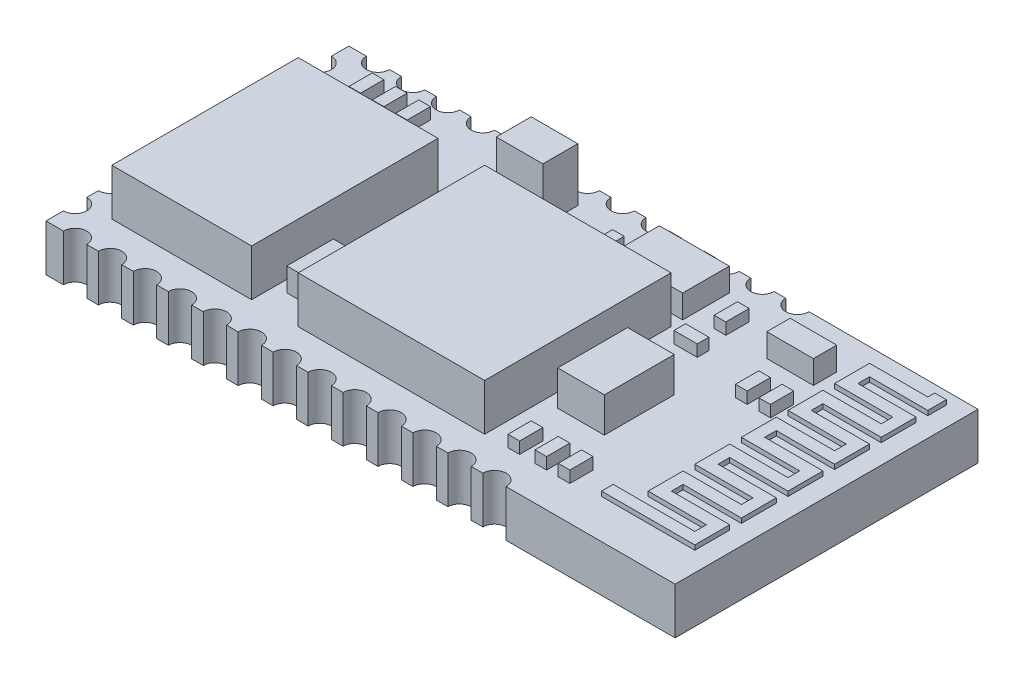
SolidWorks part; units mm, degrees
ref_plane "Front Plane" through (0, 0, 0) normal (0, 0, 1) x (1, 0, 0)
ref_plane "Top Plane" through (0, 0, 0) normal (0, 1, 0) x (1, 0, 0)
ref_plane "Right Plane" through (0, 0, 0) normal (1, 0, 0) x (0, 0, -1)
sketch "Sketch1" plane through (0, 0, 0) normal (0, 1, 0) x (1, 0, 0)
  line L1 (13.5, -6.5) -> (-13.5, -6.5)
  line L2 (13.5, -6.5) -> (13.5, 6.5)
  line L3 (13.5, 6.5) -> (-13.5, 6.5)
  line L4 (-13.5, -6.5) -> (-13.5, 6.5)
  line L5 (13.5, -6.5) -> (-13.5, 6.5) construction
  line L6 (13.5, 6.5) -> (-13.5, -6.5) construction
  point P0 (0, 0)
  dimension "D1" = 13
  dimension "D2" = 27
extrude "Boss-Extrude1" add sketch "Sketch1" along normal blind 2
sketch "Sketch2" plane through (0, 2, 0) normal (0, 1, 0) x (1, 0, 0)
  line L0 (-13.5, 6.5) -> (-13.5, -6.5) construction
  circle A0 centre (-13.5, 5.25) radius 0.5
  circle A1 centre (-13.5, 3.75) radius 0.5
  circle A2 centre (-13.5, 2.25) radius 0.5
  circle A3 centre (-13.5, 0.75) radius 0.5
  circle A4 centre (-13.5, -0.75) radius 0.5
  circle A5 centre (-13.5, -2.25) radius 0.5
  circle A6 centre (-13.5, -3.75) radius 0.5
  circle A7 centre (-13.5, -5.25) radius 0.5
  dimension "D1" = 1.25
  dimension "D2" = 2.75
  dimension "D3" = 4.25
  dimension "D4" = 5.75
  dimension "D5" = 7.25
  dimension "D6" = 8.75
  dimension "D7" = 10.25
  dimension "D8" = 11.75
extrude "Cut-Extrude7" cut sketch "Sketch2" against normal blind 2
sketch "Sketch9" plane through (0, 2, 0) normal (0, 1, 0) x (1, 0, 0)
  line L0 (13.5, 6.5) -> (-13.5, 6.5) construction
  circle A0 centre (-12.25, 6.5) radius 0.5
  circle A1 centre (-10.75, 6.5) radius 0.5
  circle A2 centre (-9.25, 6.5) radius 0.5
  circle A3 centre (-7.75, 6.5) radius 0.5
  circle A4 centre (-6.25, 6.5) radius 0.5
  circle A5 centre (-4.75, 6.5) radius 0.5
  circle A6 centre (-3.25, 6.5) radius 0.5
  circle A7 centre (-1.75, 6.5) radius 0.5
  circle A8 centre (-0.25, 6.5) radius 0.5
  circle A9 centre (1.25, 6.5) radius 0.5
  circle A10 centre (2.75, 6.5) radius 0.5
  circle A11 centre (4.25, 6.5) radius 0.5
  circle A12 centre (5.75, 6.5) radius 0.5
  circle A13 centre (-1.75, -6.5) radius 0.5
  circle A14 centre (-0.25, -6.5) radius 0.5
  circle A15 centre (-3.25, -6.5) radius 0.5
  circle A16 centre (2.75, -6.5) radius 0.5
  circle A17 centre (-7.75, -6.5) radius 0.5
  circle A18 centre (1.25, -6.5) radius 0.5
  circle A19 centre (-9.25, -6.5) radius 0.5
  circle A20 centre (-6.25, -6.5) radius 0.5
  circle A21 centre (4.25, -6.5) radius 0.5
  circle A22 centre (-12.25, -6.5) radius 0.5
  circle A23 centre (-10.75, -6.5) radius 0.5
  circle A24 centre (-4.75, -6.5) radius 0.5
  circle A25 centre (5.75, -6.5) radius 0.5
  dimension "D1" = 1.25
  dimension "D2" = 2.75
  dimension "D3" = 4.25
  dimension "D4" = 5.75
  dimension "D5" = 7.25
  dimension "D6" = 8.75
  dimension "D7" = 10.25
  dimension "D8" = 11.75
  dimension "D9" = 13.25
  dimension "D10" = 14.75
  dimension "D11" = 16.25
  dimension "D12" = 17.75
  dimension "D13" = 19.25
extrude "Cut-Extrude9" cut sketch "Sketch9" against normal blind 2
sketch "Sketch10" plane through (0, 2, 0) normal (0, 1, 0) x (1, 0, 0)
  line L1 (-12.1586, 2.9835) -> (-6.1586, 2.9835)
  line L2 (-12.1586, 2.9835) -> (-12.1586, -5.0165)
  line L3 (-12.1586, -5.0165) -> (-6.1586, -5.0165)
  line L4 (-6.1586, 2.9835) -> (-6.1586, -5.0165)
  line L5 (-4.1586, 2.9835) -> (3.8414, 2.9835)
  line L6 (-4.1586, 2.9835) -> (-4.1586, -5.0165)
  line L7 (-4.1586, -5.0165) -> (3.8414, -5.0165)
  line L8 (3.8414, 2.9835) -> (3.8414, -5.0165)
  dimension "D1" = 6
  dimension "D2" = 8
  dimension "D3" = 2
  dimension "D4" = 8
  dimension "D5" = 2
extrude "Boss-Extrude2" add sketch "Sketch10" along normal blind 2
sketch "Sketch12" plane through (0, 2, 0) normal (0, 1, 0) x (1, 0, 0)
  line L0 (3.8414, 2.9835) -> (-4.1586, 2.9835) construction
  line L1 (0.8414, 5.4835) -> (3.8414, 5.4835)
  line L2 (0.8414, 5.4835) -> (0.8414, 3.4835)
  line L3 (0.8414, 3.4835) -> (3.8414, 3.4835)
  line L4 (3.8414, 5.4835) -> (3.8414, 3.4835)
  line L6 (3.8414, -5.0165) -> (3.8414, 2.9835) construction
  dimension "D1" = 2
  dimension "D2" = 3
  dimension "D3" = 0.5
  dimension "D4" = 0
extrude "Boss-Extrude3" add sketch "Sketch12" along normal blind 1
sketch "Sketch13" plane through (0, 2, 0) normal (0, 1, 0) x (1, 0, 0)
  line L0 (0.8414, 5.4835) -> (0.8414, 3.4835) construction
  line L1 (-4.6586, 5.4835) -> (-2.6586, 5.4835)
  line L2 (-4.6586, 5.4835) -> (-4.6586, 3.9835)
  line L3 (-4.6586, 3.9835) -> (-2.6586, 3.9835)
  line L4 (-2.6586, 5.4835) -> (-2.6586, 3.9835)
  line L5 (0.8414, 5.4835) -> (0.8414, 3.4835) construction
  line L7 (3.8414, 2.9835) -> (-4.1586, 2.9835) construction
  point P9 (0.8414, 4.4835)
  dimension "D1" = 1.5
  dimension "D2" = 2
  dimension "D3" = 3.5
  dimension "D4" = 1
extrude "Boss-Extrude4" add sketch "Sketch13" along normal blind 2.3
sketch "Sketch14" plane through (0, 2, 0) normal (0, 1, 0) x (1, 0, 0)
  line L0 (-13.5, 6.5) -> (-13.5, 5.75) construction
  line L1 (-11, 4.5) -> (-11.5, 4.5)
  line L2 (-11, 4.5) -> (-11, 5.5)
  line L3 (-11, 5.5) -> (-11.5, 5.5)
  line L4 (-11.5, 4.5) -> (-11.5, 5.5)
  line L5 (-10, 4.5) -> (-10, 5.5)
  line L6 (-10.5, 4.5) -> (-10.5, 5.5)
  line L7 (-10, 4.5) -> (-10.5, 4.5)
  line L8 (-9.5, 4.5) -> (-9.5, 5.5)
  line L9 (-9, 4.5) -> (-9.5, 4.5)
  line L10 (-9, 4.5) -> (-9, 5.5)
  line L11 (-9, 5.5) -> (-9.5, 5.5)
  line L12 (6.5, -5.0165) -> (6.5, -4.0165)
  line L13 (7.5, -5.0165) -> (7.5, -4.0165)
  line L14 (7.5, -4.0165) -> (7, -4.0165)
  line L15 (6.5, -4.0165) -> (6, -4.0165)
  line L16 (6.5, -5.0165) -> (6, -5.0165)
  line L17 (7.5, -5.0165) -> (7, -5.0165)
  line L18 (7, -5.0165) -> (7, -4.0165)
  line L19 (6, -5.0165) -> (6, -4.0165)
  line L20 (5.3414, -5.0165) -> (4.8414, -5.0165)
  line L21 (5.3414, -5.0165) -> (5.3414, -4.0165)
  line L22 (4.8414, -5.0165) -> (4.8414, -4.0165)
  line L23 (5.3414, -4.0165) -> (4.8414, -4.0165)
  line L24 (9.3661, 2.7256) -> (8.8661, 2.7256)
  line L25 (9.3661, 1.7256) -> (8.8661, 1.7256)
  line L26 (8.8661, 1.7256) -> (8.8661, 2.7256)
  line L27 (9.3661, 1.7256) -> (9.3661, 2.7256)
  line L28 (8.3661, 1.7256) -> (8.3661, 2.7256)
  line L29 (8.3661, 1.7256) -> (7.8661, 1.7256)
  line L30 (7.8661, 1.7256) -> (7.8661, 2.7256)
  line L31 (8.3661, 2.7256) -> (7.8661, 2.7256)
  line L32 (-5.4086, 2.5) -> (-5.4086, 3.5)
  line L33 (-4.9086, 2.5) -> (-5.4086, 2.5)
  line L34 (-4.9086, 3.5) -> (-5.4086, 3.5)
  line L35 (-4.9086, 2.5) -> (-4.9086, 3.5)
  line L36 (13.5, -6.5) -> (13.5, 6.5) construction
  line L37 (-5.25, 6.5) -> (-5.75, 6.5) construction
  line L38 (3.8414, -5.0165) -> (3.8414, 2.9835) construction
  line L39 (4.8414, 3.8366) -> (4.8414, 4.8366)
  line L40 (-4.9086, 0.5) -> (-5.4086, 0.5)
  line L41 (-5.4086, -0.5) -> (-5.4086, 0.5)
  line L42 (-4.9086, -0.5) -> (-4.9086, 0.5)
  line L43 (-4.9086, -0.5) -> (-5.4086, -0.5)
  line L44 (-4.9086, -4.1379) -> (-4.9086, -2.6379)
  line L45 (-4.9086, -2.6379) -> (-5.4086, -2.6379)
  line L46 (-5.4086, -4.1379) -> (-5.4086, -2.6379)
  line L47 (-4.9086, -4.1379) -> (-5.4086, -4.1379)
  line L48 (-6.1586, -5.0165) -> (-6.1586, 2.9835) construction
  line L49 (5.3414, 4.8366) -> (4.8414, 4.8366)
  line L50 (5.3414, 3.8366) -> (5.3414, 4.8366)
  line L51 (5.3414, 3.8366) -> (4.8414, 3.8366)
  line L52 (-0.0202, 3.8366) -> (-0.5202, 3.8366)
  line L53 (-0.0202, 4.8366) -> (-0.5202, 4.8366)
  line L54 (-0.0202, 3.8366) -> (-0.0202, 4.8366)
  line L55 (-0.5202, 3.8366) -> (-0.5202, 4.8366)
  line L56 (7.5, 4.196) -> (7.5, 3.696)
  line L57 (9, 3.696) -> (7.5, 3.696)
  line L58 (9, 4.196) -> (7.5, 4.196)
  line L59 (9, 4.196) -> (9, 3.696)
  line L60 (5.5459, 2.9031) -> (4.5459, 2.9031)
  line L61 (4.5459, -0.6918) -> (5.5459, -0.6918)
  line L62 (4.5459, -0.6918) -> (4.5459, -2.6918)
  line L63 (4.5459, -2.6918) -> (5.5459, -2.6918)
  line L64 (5.5459, -0.6918) -> (5.5459, -2.6918)
  line L65 (5.5459, 2.4031) -> (4.5459, 2.4031)
  line L66 (4.5459, 2.9031) -> (4.5459, 2.4031)
  line L67 (5.5459, 2.9031) -> (5.5459, 2.4031)
  line L68 (-10.5, 5.5) -> (-10, 5.5)
  line L69 (-9.5, 5.5) -> (-9, 5.5)
  dimension "D1" = 0.5
  dimension "D2" = 1
  dimension "D3" = 2
  dimension "D4" = 1
  dimension "D5" = 1
  dimension "D6" = 0.5
  dimension "D7" = 1
  dimension "D8" = 0.5
  dimension "D9" = 0.5
  dimension "D10" = 0.5
  dimension "D11" = 0.5
  dimension "D12" = 1
  dimension "D13" = 0.5
  dimension "D14" = 0.75
  dimension "D15" = 1
  dimension "D16" = 1
  dimension "D17" = 0.5
  dimension "D18" = 1
  dimension "D19" = 0.5
  dimension "D20" = 6
  dimension "D21" = 0.75
  dimension "D22" = 0.75
  dimension "D23" = 3
  dimension "D24" = 1
  dimension "D25" = 2
  dimension "D26" = 1
  dimension "D27" = 1.5
  dimension "D28" = 1
  dimension "D29" = 2
extrude "Boss-Extrude6" add sketch "Sketch14" along normal blind 0.5 contours L10 L11 L8 L9 | L43 L42 L40 L41 | L51 L50 L49 L39 | L28 L31 L30 L29 | L25 L27 L24 L26 | L19 L16 L12 L15 | L2 L3 L4 L1 | L6 L68 L5 L7 | L54 L53 L55 L52 | L32 L34 L35 L33 | L60 L66 L65 L67 | L18 L14 L13 L17 | L21 L23 L22 L20
sketch "Sketch15" plane through (0, 2, 0) normal (0, 1, 0) x (1, 0, 0)
  line L0 (7.0844, 3.8532) -> (7.0844, 4.8532)
  line L1 (-5.6604, -2.0048) -> (-4.6604, -2.0048)
  line L2 (-5.6604, -2.0048) -> (-5.6604, -4.0048)
  line L3 (-5.6604, -4.0048) -> (-4.6604, -4.0048)
  line L4 (-4.6604, -2.0048) -> (-4.6604, -4.0048)
  line L5 (7.0844, 3.8532) -> (9.0844, 3.8532)
  line L6 (7.0844, 4.8532) -> (9.0844, 4.8532)
  line L7 (9.0844, 3.8532) -> (9.0844, 4.8532)
  dimension "D1" = 1
  dimension "D2" = 2
  dimension "D3" = 1
  dimension "D4" = 2
extrude "Boss-Extrude7" add sketch "Sketch15" along normal blind 1
sketch "Sketch16" plane through (0, 2, 0) normal (0, 1, 0) x (1, 0, 0)
  line L1 (4.4442, 0.5186) -> (6.4442, 0.5186)
  line L2 (4.4442, 0.5186) -> (4.4442, -2.4814)
  line L3 (4.4442, -2.4814) -> (6.4442, -2.4814)
  line L4 (6.4442, 0.5186) -> (6.4442, -2.4814)
  dimension "D1" = 2
  dimension "D2" = 3
extrude "Boss-Extrude8" add sketch "Sketch16" along normal blind 1.5
sketch "Sketch17" plane through (0, 2, 0) normal (0, 1, 0) x (1, 0, 0)
  line L0 (12.1639, 5.6806) -> (9.6639, 5.6806)
  line L1 (9.6639, 5.6806) -> (9.6639, 4.1806)
  line L2 (10.1639, 5.1806) -> (12.6639, 5.1806)
  line L3 (10.1639, 5.1806) -> (10.1639, 4.6806)
  line L4 (9.6639, 4.1806) -> (12.1639, 4.1806)
  line L5 (9.6639, 3.6806) -> (9.6639, 2.1806)
  line L6 (10.1639, 3.1806) -> (10.1639, 2.6806)
  line L7 (12.1639, 3.6806) -> (9.6639, 3.6806)
  line L8 (10.1639, 3.1806) -> (12.6639, 3.1806)
  line L9 (9.6639, 2.1806) -> (12.1639, 2.1806)
  line L10 (12.6639, 3.1806) -> (12.6639, 4.6806)
  line L11 (10.1639, 4.6806) -> (12.6639, 4.6806)
  line L12 (12.1639, 4.1806) -> (12.1639, 3.6806)
  line L13 (10.1639, 2.6806) -> (12.6639, 2.6806)
  line L14 (9.6639, 1.6806) -> (9.6639, 0.1806)
  line L15 (10.1639, -0.8194) -> (12.6639, -0.8194)
  line L16 (12.1639, 0.1806) -> (12.1639, -0.3194)
  line L17 (9.6639, -0.3194) -> (9.6639, -1.8194)
  line L18 (9.6639, 0.1806) -> (12.1639, 0.1806)
  line L19 (9.6639, -1.8194) -> (12.1639, -1.8194)
  line L20 (10.1639, -0.8194) -> (10.1639, -1.3194)
  line L21 (12.6639, -0.8194) -> (12.6639, 0.6806)
  line L22 (10.1639, 1.1806) -> (12.6639, 1.1806)
  line L23 (12.1639, -0.3194) -> (9.6639, -0.3194)
  line L24 (12.1639, 1.6806) -> (9.6639, 1.6806)
  line L25 (10.1639, 0.6806) -> (12.6639, 0.6806)
  line L26 (10.1639, -1.3194) -> (12.6639, -1.3194)
  line L27 (10.1639, 1.1806) -> (10.1639, 0.6806)
  line L28 (12.1639, 1.6806) -> (12.1639, 2.1806)
  line L29 (12.6639, 2.6806) -> (12.6639, 1.1806)
  line L30 (12.6639, -2.8194) -> (12.6639, -1.3194)
  line L31 (9.6639, -3.8194) -> (12.1639, -3.8194)
  line L32 (10.1639, -3.3194) -> (12.6639, -3.3194)
  line L33 (10.1639, -2.8194) -> (12.6639, -2.8194)
  line L34 (12.1639, -2.3194) -> (9.6639, -2.3194)
  line L35 (12.1639, -1.8194) -> (12.1639, -2.3194)
  line L36 (9.6639, -2.3194) -> (9.6639, -3.8194)
  line L37 (10.1639, -2.8194) -> (10.1639, -3.3194)
  line L38 (8.6639, -4.8194) -> (12.6639, -4.8194)
  line L39 (12.1639, -3.8194) -> (12.1639, -4.3194)
  line L40 (12.1639, -4.3194) -> (8.6639, -4.3194)
  line L41 (12.6639, -4.8194) -> (12.6639, -3.3194)
  line L42 (8.6639, -4.8194) -> (8.6639, -4.3194)
  line L43 (12.6639, 5.1806) -> (12.6639, 5.975)
  line L44 (12.6639, 5.975) -> (12.1639, 5.975)
  line L45 (12.1639, 5.975) -> (12.1639, 5.6806)
  dimension "D1" = 2.5
  dimension "D2" = 1.5
  dimension "D3" = 2.5
  dimension "D4" = 0.5
  dimension "D5" = 0.5
  dimension "D6" = 0.5
  dimension "D7" = 2.5
  dimension "D8" = 2.5
  dimension "D9" = 0.5
  dimension "D10" = 1.5
  dimension "D11" = 0.5
  dimension "D12" = 2.5
  dimension "D13" = 1.5
  dimension "D14" = 2.5
  dimension "D15" = 0.5
  dimension "D16" = 0.5
  dimension "D17" = 0.5
  dimension "D18" = 2.5
  dimension "D19" = 2.5
  dimension "D20" = 0.5
  dimension "D21" = 1.5
  dimension "D22" = 0.5
  dimension "D23" = 0.5
  dimension "D24" = 2.5
  dimension "D25" = 1.5
  dimension "D26" = 0.5
  dimension "D27" = 0.5
  dimension "D28" = 4
  dimension "D29" = 1.5
  dimension "D30" = 0.5
  dimension "D31" = 0.5
  dimension "D32" = 3.5
extrude "Boss-Extrude9" add sketch "Sketch17" along normal blind 0.2
